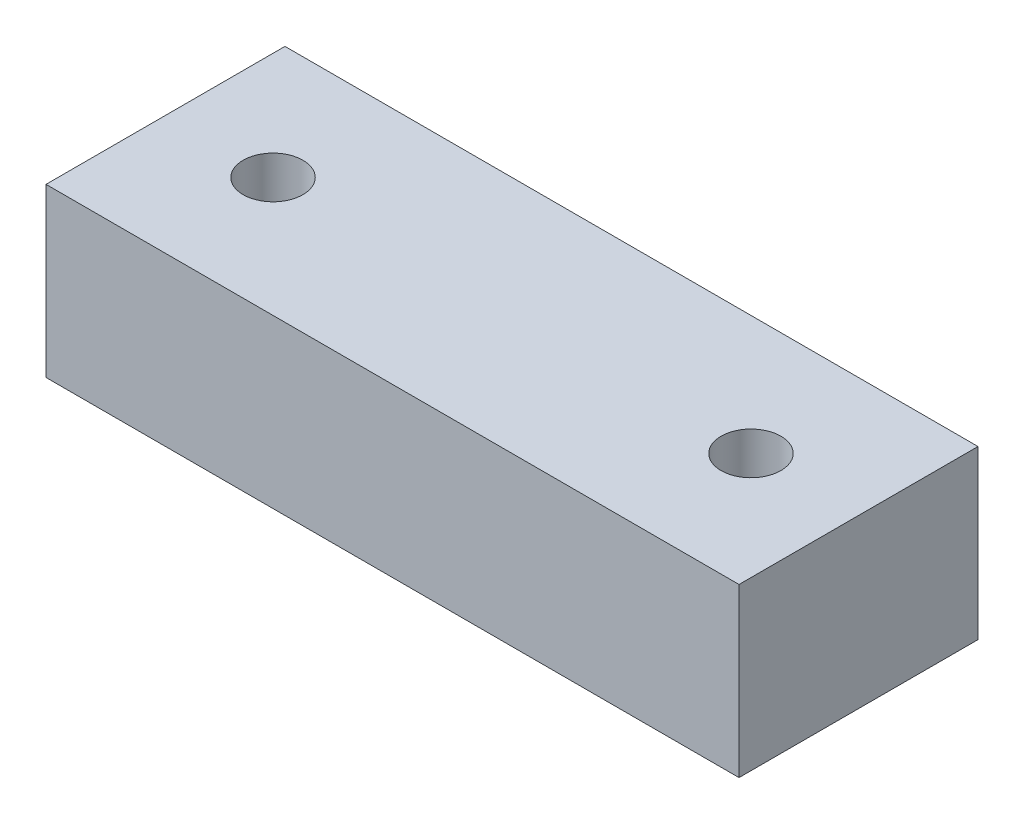
SolidWorks part; units mm, degrees
ref_plane "Front Plane" through (0, 0, 0) normal (0, 0, 1) x (1, 0, 0)
ref_plane "Top Plane" through (0, 0, 0) normal (0, 1, 0) x (1, 0, 0)
ref_plane "Right Plane" through (0, 0, 0) normal (1, 0, 0) x (0, 0, -1)
sketch "Sketch1" plane through (0, 0, 0) normal (0, 1, 0) x (1, 0, 0)
  line L1 (0, 0) -> (36.83, 0)
  line L2 (0, 0) -> (0, -12.7)
  line L3 (0, -12.7) -> (36.83, -12.7)
  line L4 (36.83, 0) -> (36.83, -12.7)
  circle A0 centre (5.715, -6.35) radius 1.5875
  circle A1 centre (31.115, -6.35) radius 1.5875
  point P9 (18.415, 0)
  point P10 (0, -6.35)
  dimension "D7" = 3.175
  dimension "D8" = 3.175
  dimension "D1" = 36.83
  dimension "D2" = 12.7
  dimension "D3" = 0
  dimension "D4" = 0
  dimension "D5" = 12.7
  dimension "D6" = 12.7
extrude "Boss-Extrude1" add sketch "Sketch1" along normal blind 8.89
